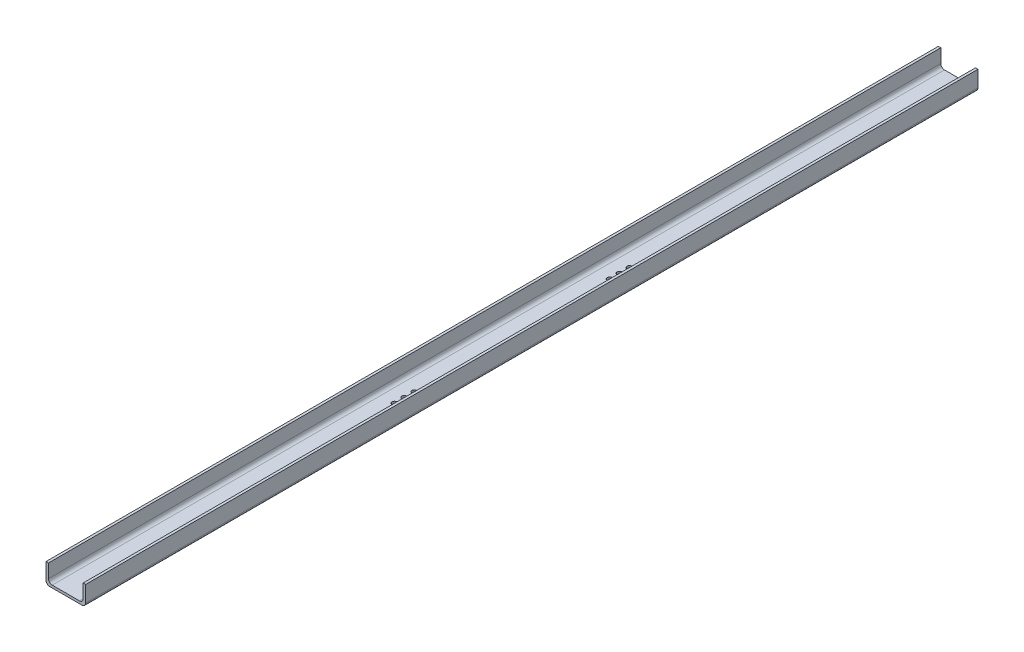
SolidWorks part; units mm, degrees
material "Cast Alloy Steel"
ref_plane "Front Plane" through (0, 0, 0) normal (0, 0, 1) x (1, 0, 0)
ref_plane "Top Plane" through (0, 0, 0) normal (0, 1, 0) x (1, 0, 0)
ref_plane "Right Plane" through (0, 0, 0) normal (1, 0, 0) x (0, 0, -1)
sketch "Sketch1" plane through (0, 0, 0) normal (0, 0, 1) x (1, 0, 0)
  line L0 (-25.4, 25.4) -> (-25.4, 0)
  line L1 (-25.4, 0) -> (25.4, 0)
  line L2 (25.4, 0) -> (25.4, 25.4)
  line L3 (25.4, 25.4) -> (22.225, 25.4)
  line L4 (22.225, 25.4) -> (22.225, 3.175)
  line L5 (22.225, 3.175) -> (-22.225, 3.175)
  line L6 (-22.225, 3.175) -> (-22.225, 25.4)
  line L7 (-22.225, 25.4) -> (-25.4, 25.4)
  line L8 (0, 17.6539) -> (0, -12.3397) construction
  dimension "D1" = 50.8
  dimension "D2" = 25.4
  dimension "D3" = 3.175
  dimension "D4" = 3.175
extrude "Boss-Extrude1" add sketch "Sketch1" along normal blind 1143
fillet "Fillet1" radius 4.7625 2 edges at (22.225, 3.175, 571.5) (-22.225, 3.175, 571.5)
fillet "Fillet2" radius 4.7625 2 edges at (25.4, 0, 571.5) (-25.4, 0, 571.5)
sketch "Sketch2" plane through (0, 3.175, 0) normal (0, 1, 0) x (1, 0, 0)
  line L0 (0, -1143) -> (0, 0) construction
  line L1 (17.4625, -1143) -> (-17.4625, -1143) construction
  point P5 (0, -571.5)
  point P6 (0, -433.7)
  point P7 (0, -709.3)
  point P8 (-366.6401, -1056.3687)
  point P9 (0, -696.6)
  point P10 (0, -446.4)
  point P11 (0, -421)
  point P12 (0, -722)
  dimension "D1" = 137.8
  dimension "D2" = 137.8
  dimension "D3" = 25.4
  dimension "D4" = 12.7
  dimension "D5" = 25.4
  dimension "D6" = 12.7
hole_wizard "1/4 (0.25) Diameter Hole1" positions "Sketch3" profile "Sketch4" hole size "1/4" standard "ANSI Inch" end condition through all
sketch "Sketch3" plane through (0, 3.175, 0) normal (0, 1, 0) x (1, 0, 0)
  point P0 (0, -722)
  point P3 (0, -709.3)
  point P6 (0, -696.6)
  point P9 (0, -446.4)
  point P12 (0, -433.7)
  point P15 (0, -421)
sketch "Sketch4" plane through (0, 3.175, 722) normal (1, 0, 0) x (0, 0, 1)
  line L0 (0, 0) -> (0, 3.175)
  line L1 (0, 3.175) -> (3.175, 3.175)
  line L2 (3.175, 3.175) -> (3.175, 0)
  line L5 (3.175, 0) -> (0, 0)
  line L11 (0, -6.35) -> (0, 107.95) construction
  dimension "Thru Hole Dia." = 6.35
  dimension "Thru Hole Depth" = 3.175
equation "\"D1@Sketch2\"=\"D2@Sketch2\""
